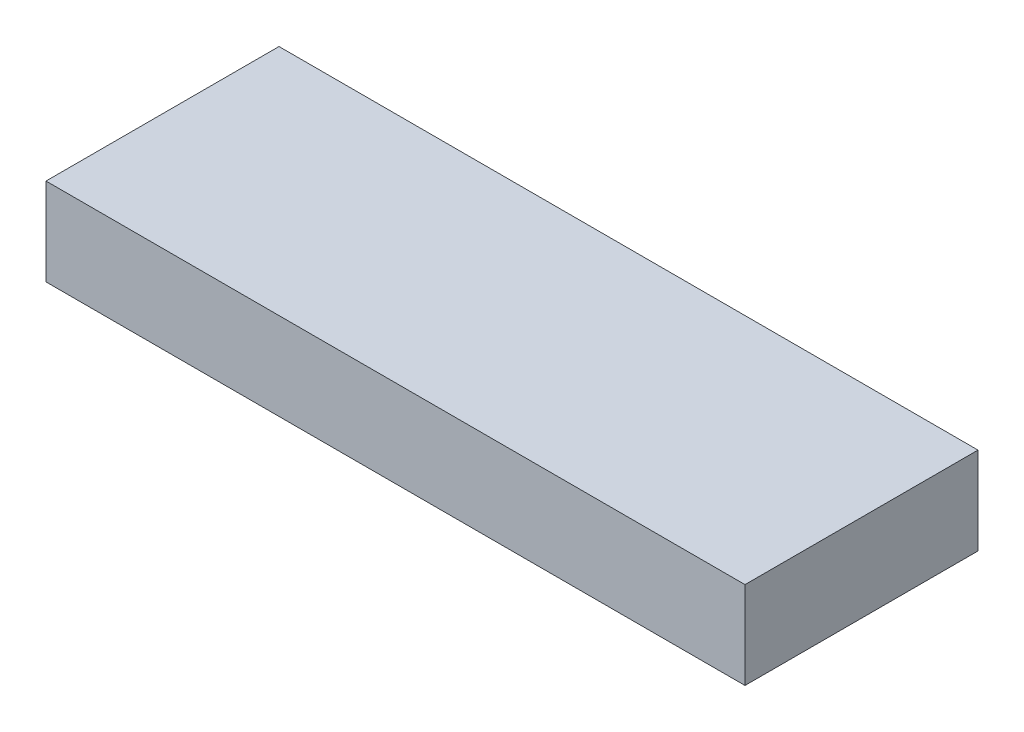
SolidWorks part; units mm, degrees
ref_plane "Front Plane" through (0, 0, 0) normal (0, 0, 1) x (1, 0, 0)
ref_plane "Top Plane" through (0, 0, 0) normal (0, 1, 0) x (1, 0, 0)
ref_plane "Right Plane" through (0, 0, 0) normal (1, 0, 0) x (0, 0, -1)
sketch "Sketch1" plane through (0, 0, 0) normal (0, 1, 0) x (1, 0, 0)
  line L1 (-4.0885, 2.4159) -> (7.9115, 2.4159)
  line L2 (-4.0885, 2.4159) -> (-4.0885, -1.5841)
  line L3 (-4.0885, -1.5841) -> (7.9115, -1.5841)
  line L4 (7.9115, 2.4159) -> (7.9115, -1.5841)
  dimension "D1" = 12
  dimension "D2" = 4
extrude "Boss-Extrude1" add sketch "Sketch1" along normal blind 1.5
